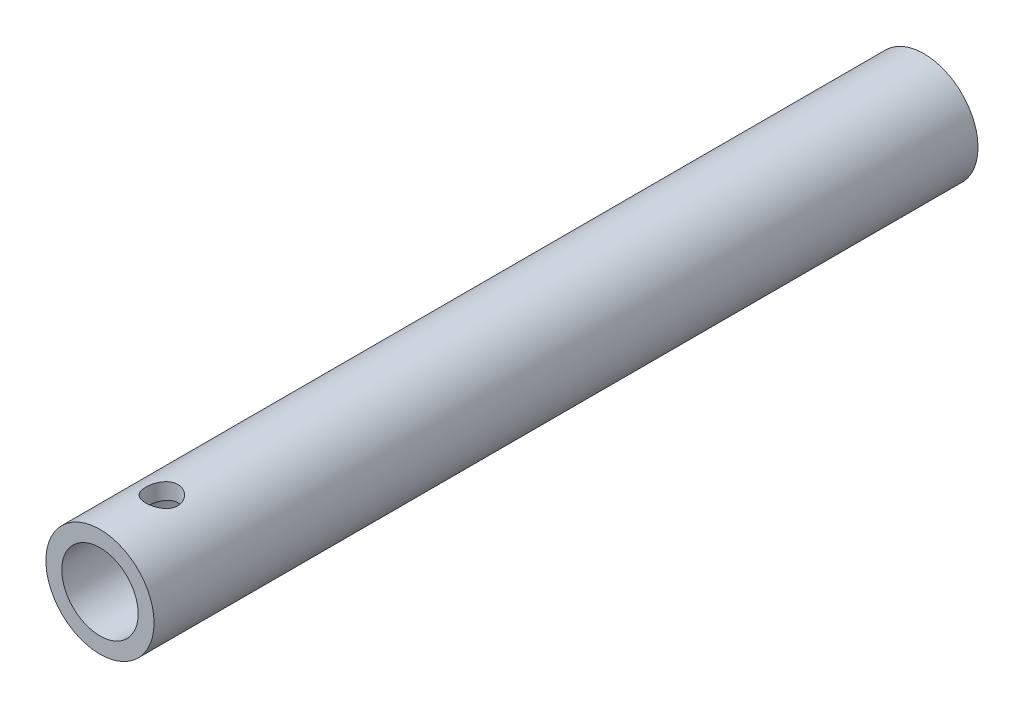
SolidWorks part; units mm, degrees
ref_plane "Front Plane" through (0, 0, 0) normal (0, 0, 1) x (1, 0, 0)
ref_plane "Top Plane" through (0, 0, 0) normal (0, 1, 0) x (1, 0, 0)
ref_plane "Right Plane" through (0, 0, 0) normal (1, 0, 0) x (0, 0, -1)
sketch "Sketch1" plane through (0, 0, 0) normal (0, 0, 1) x (1, 0, 0)
  circle A0 centre (0, 0) radius 13.335
  dimension "Pipe OD" = 26.67
extrude "Extrude-Thin1" add sketch "Sketch1" along normal mid plane 203.2 thin thin type one direction reverse wall 3.9116
sketch "Sketch2" plane through (0, 0, 0) normal (0, 1, 0) x (1, 0, 0)
  line L0 (-13.335, -101.6) -> (13.335, -101.6) construction
  line L1 (0, -86.36) -> (0, 0) construction
  circle A0 centre (0, -86.36) radius 3.9687
  dimension "D1" = 7.9375
  dimension "D2" = 15.24
extrude "Cut-Extrude1" cut sketch "Sketch2" against normal through all both and the other way through all
